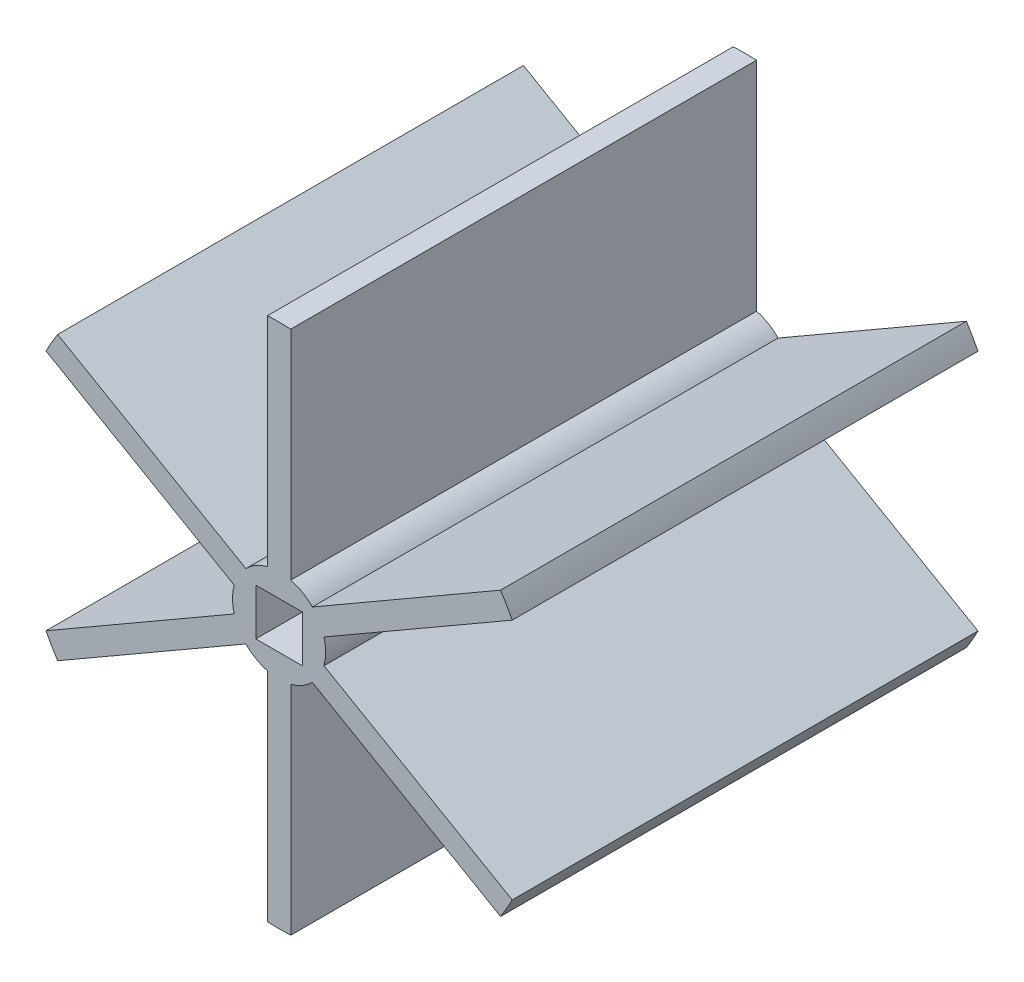
SolidWorks part; units mm, degrees
material "ABS"
ref_plane "Plan de face" through (0, 0, 0) normal (0, 0, 1) x (1, 0, 0)
ref_plane "Plan de dessus" through (0, 0, 0) normal (0, 1, 0) x (1, 0, 0)
ref_plane "Plan de droite" through (0, 0, 0) normal (1, 0, 0) x (0, 0, -1)
sketch "Esquisse1" plane through (0, 0, 0) normal (0, 0, 1) x (1, 0, 0)
  line L0 (0, 0) -> (0, 28.2) construction
  line L1 (2.5, -2.5) -> (-2.5, -2.5)
  line L2 (2.5, -2.5) -> (2.5, 2.5)
  line L3 (2.5, 2.5) -> (-2.5, 2.5)
  line L4 (-2.5, -2.5) -> (-2.5, 2.5)
  line L5 (2.5, -2.5) -> (-2.5, 2.5) construction
  line L6 (2.5, 2.5) -> (-2.5, -2.5) construction
  line L7 (1.25, 28.1723) -> (1.25, 4.8412)
  line L8 (-1.25, 28.1723) -> (-1.25, 4.8412)
  line L9 (25.0229, 13.0036) -> (4.8176, 1.3381)
  line L10 (23.7729, 15.1687) -> (3.5676, 3.5031)
  line L11 (23.7729, -15.1687) -> (3.5676, -3.5031)
  line L12 (25.0229, -13.0036) -> (4.8176, -1.3381)
  line L13 (-1.25, -28.1723) -> (-1.25, -4.8412)
  line L14 (1.25, -28.1723) -> (1.25, -4.8412)
  line L15 (-25.0229, -13.0036) -> (-4.8176, -1.3381)
  line L16 (-23.7729, -15.1687) -> (-3.5676, -3.5031)
  line L17 (-23.7729, 15.1687) -> (-3.5676, 3.5031)
  line L18 (-25.0229, 13.0036) -> (-4.8176, 1.3381)
  circle A0 centre (0, 0) radius 28.2 construction
  arc A1 (-1.25, 4.8412) -> (-3.5676, 3.5031) centre (0, 0) ccw
  arc A2 (-1.25, 28.1723) -> (1.25, 28.1723) centre (0, 0) cw
  arc A3 (3.5676, 3.5031) -> (1.25, 4.8412) centre (0, 0) ccw
  arc A4 (23.7729, 15.1687) -> (25.0229, 13.0036) centre (0, 0) cw
  arc A6 (25.0229, -13.0036) -> (23.7729, -15.1687) centre (0, 0) cw
  arc A7 (1.25, -4.8412) -> (3.5676, -3.5031) centre (0, 0) ccw
  arc A8 (1.25, -28.1723) -> (-1.25, -28.1723) centre (0, 0) cw
  arc A9 (-3.5676, -3.5031) -> (-1.25, -4.8412) centre (0, 0) ccw
  arc A10 (-23.7729, -15.1687) -> (-25.0229, -13.0036) centre (0, 0) cw
  arc A11 (-4.8176, 1.3381) -> (-4.8176, -1.3381) centre (0, 0) ccw
  arc A12 (-25.0229, 13.0036) -> (-23.7729, 15.1687) centre (0, 0) cw
  arc A13 (-4.8176, 1.3381) -> (-4.8176, -1.3381) centre (0, 0) ccw
  arc A14 (-4.8176, 1.3381) -> (-4.8176, -1.3381) centre (0, 0) ccw
  arc A15 (-4.8176, 1.3381) -> (-4.8176, -1.3381) centre (0, 0) ccw
  arc A16 (-4.8176, 1.3381) -> (-4.8176, -1.3381) centre (0, 0) ccw
  arc A17 (-4.8176, 1.3381) -> (-4.8176, -1.3381) centre (0, 0) ccw
  arc A18 (3.5676, 3.5031) -> (1.25, 4.8412) centre (0, 0) ccw
  arc A19 (3.5676, 3.5031) -> (1.25, 4.8412) centre (0, 0) ccw
  arc A20 (3.5676, 3.5031) -> (1.25, 4.8412) centre (0, 0) ccw
  arc A21 (4.8176, -1.3381) -> (4.8176, 1.3381) centre (0, 0) ccw [skipped]
  arc A22 (4.8176, -1.3381) -> (4.8176, 1.3381) centre (0, 0) ccw
  arc A23 (4.8176, -1.3381) -> (4.8176, 1.3381) centre (0, 0) ccw
  arc A24 (4.8176, -1.3381) -> (4.8176, 1.3381) centre (0, 0) ccw
  arc A25 (4.8176, -1.3381) -> (4.8176, 1.3381) centre (0, 0) ccw
  arc A26 (1.25, -4.8412) -> (3.5676, -3.5031) centre (0, 0) ccw
  arc A27 (1.25, -4.8412) -> (3.5676, -3.5031) centre (0, 0) ccw
  arc A28 (1.25, -4.8412) -> (3.5676, -3.5031) centre (0, 0) ccw
  arc A29 (-3.5676, -3.5031) -> (-1.25, -4.8412) centre (0, 0) ccw
  arc A30 (-3.5676, -3.5031) -> (-1.25, -4.8412) centre (0, 0) ccw
  arc A31 (-3.5676, -3.5031) -> (-1.25, -4.8412) centre (0, 0) ccw
  arc A32 (-3.5676, -3.5031) -> (-1.25, -4.8412) centre (0, 0) ccw
  arc A33 (-3.5676, -3.5031) -> (-1.25, -4.8412) centre (0, 0) ccw
  arc A34 (-1.25, 4.8412) -> (-3.5676, 3.5031) centre (0, 0) ccw
  arc A35 (-1.25, 4.8412) -> (-3.5676, 3.5031) centre (0, 0) ccw
  arc A36 (-1.25, 4.8412) -> (-3.5676, 3.5031) centre (0, 0) ccw
  arc A37 (-1.25, 4.8412) -> (-3.5676, 3.5031) centre (0, 0) ccw
  arc A38 (-1.25, 4.8412) -> (-3.5676, 3.5031) centre (0, 0) ccw
  arc A39 (3.5676, 3.5031) -> (1.25, 4.8412) centre (0, 0) ccw
  arc A40 (3.5676, 3.5031) -> (1.25, 4.8412) centre (0, 0) ccw
  arc A41 (4.8176, -1.3381) -> (4.8176, 1.3381) centre (0, 0) ccw
  arc A42 (1.25, -4.8412) -> (3.5676, -3.5031) centre (0, 0) ccw
  arc A43 (1.25, -4.8412) -> (3.5676, -3.5031) centre (0, 0) ccw
  point P0 (0, 0)
  point P35 (0, 0)
  dimension "D2" = 56.4
  dimension "D3" = 10
  dimension "D1" = 5
  dimension "D4" = 2.5
  dimension "D5" = 6
extrude "Boss.-Extru.1" add sketch "Esquisse1" along normal mid plane 50 contours L12 A22 L9 A4 L10 A3 L7 A2 L8 A1 L17 A12 L18 A11 L15 A10 L16 A9 L13 A8 L14 A7 L11 A6 L1 L4 L3 L2
sketch "Esquisse2" plane through (0, 0, -25) normal (0, 0, -1) x (-1, 0, 0)
  line L0 (-2.5, -2.5) -> (2.5, -2.5) construction
  line L1 (2.5, -2.5) -> (2.5, 2.5) construction
  line L2 (-2.5, 2.5) -> (2.5, 2.5) construction
  line L3 (-2.5, -2.5) -> (-2.5, 2.5) construction
  line L4 (-2.5, -2.5) -> (2.5, -2.5)
  line L5 (2.5, -2.5) -> (2.5, 2.5)
  line L6 (-2.5, 2.5) -> (2.5, 2.5)
  line L7 (-2.5, -2.5) -> (-2.5, 2.5)
  circle A0 centre (0, 0) radius 26
  dimension "D1" = 52
extrude "Boss.-Extru.2" [suppressed] add sketch "Esquisse2" along normal blind 3
mirror "Symétrie1" [suppressed] about plane through (0, 0, 0) normal (0, 0, 1)
sketch "Esquisse3" plane through (0, 0, 0) normal (0, 1, 0) x (1, 0, 0)
  line L1 (-25.0229, -25) -> (25.0229, -25) construction
  line L2 (-25.0229, -25) -> (-25.0229, 25) construction
  line L3 (-25.0229, 25) -> (25.0229, 25) construction
  line L4 (25.0229, -25) -> (25.0229, 25) construction
  dimension "D1" = 50.0458
  dimension "D2" = 50
ref_plane "Plan1" through (-25.0229, 0, 0) normal (1, 0, 0) x (0, 0, -1)
ref_plane "Plan2" through (25.0229, 0, 0) normal (1, 0, 0) x (0, 0, -1)
